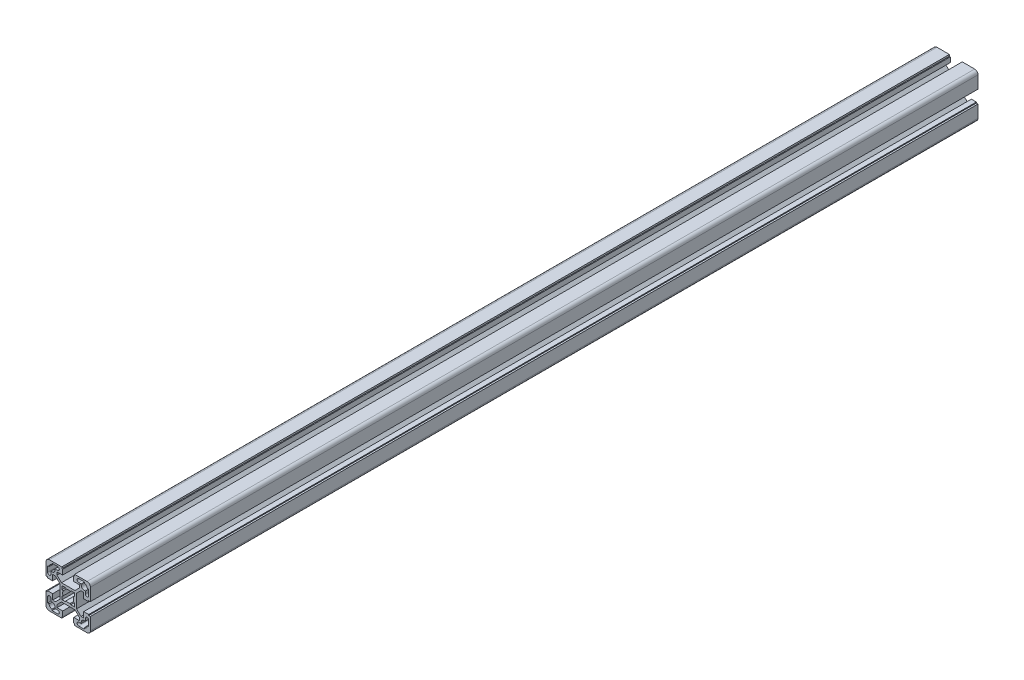
SolidWorks part; units mm, degrees
material "6061 Alloy"
ref_plane "Front Plane" through (0, 0, 0) normal (0, 0, 1) x (1, 0, 0)
ref_plane "Top Plane" through (0, 0, 0) normal (0, 1, 0) x (1, 0, 0)
ref_plane "Right Plane" through (0, 0, 0) normal (1, 0, 0) x (0, 0, -1)
sketch "Sketch1" plane through (0, 0, 0) normal (0, 0, 1) x (1, 0, 0)
  line L0 (5.8, -20) -> (17, -20)
  line L1 (14, -10.05) -> (11.4642, -10.05)
  line L2 (0, -21.1722) -> (0, 18.817) construction
  line L3 (0, 21.1722) -> (0, -18.817) construction
  line L4 (14.5, -18.5) -> (9.5, -18.5)
  line L5 (18.5, 5) -> (14, 5)
  line L6 (6.0858, -7.5) -> (10.05, -11.4642)
  line L7 (20, 5.8) -> (18.5, 5.8)
  line L8 (14, 5) -> (14, 10.05)
  line L9 (18.5, 5.8) -> (18.5, 5)
  line L10 (18.5, 14.5) -> (17.25, 14.5)
  line L11 (14.5, 11.75) -> (15.5, 11.75)
  line L12 (14.5, 17.25) -> (14.5, 18.5)
  line L13 (18.5, 9.5) -> (18.5, 14.5)
  line L14 (15.5, 11.75) -> (15.5, 9.5)
  line L15 (20, 17) -> (20, 5.8)
  line L16 (5.5, 5.5) -> (2.3979, 5.5)
  line L17 (2.3979, 5.5) -> (1.9983, 4.5833)
  line L18 (5.5, 2.3979) -> (5.5, 5.5)
  line L19 (4.5833, 1.9983) -> (5.5, 2.3979)
  line L20 (5, -14) -> (5, -18.5)
  line L21 (11.4642, 10.05) -> (7.5, 6.0858)
  line L22 (-6.0858, 7.5) -> (6.0858, 7.5)
  line L23 (11.75, 15.5) -> (11.75, 14.5)
  line L24 (5, -18.5) -> (5.8, -18.5)
  line L25 (5.8, -18.5) -> (5.8, -20)
  line L26 (10.05, -11.4642) -> (10.05, -14)
  line L27 (10.05, -14) -> (5, -14)
  line L28 (9.5, -15.5) -> (11.75, -15.5)
  line L29 (11.75, -15.5) -> (11.75, -14.5)
  line L30 (9.5, 15.5) -> (11.75, 15.5)
  line L31 (10.05, 14) -> (5, 14)
  line L32 (10.05, 11.4642) -> (10.05, 14)
  line L33 (5.8, 18.5) -> (5.8, 20)
  line L34 (5, 18.5) -> (5.8, 18.5)
  line L35 (7.5, -6.0858) -> (7.5, 6.0858)
  line L36 (5, 14) -> (5, 18.5)
  line L37 (6.0858, 7.5) -> (10.05, 11.4642)
  line L38 (14.5, 18.5) -> (9.5, 18.5)
  line L39 (14, 10.05) -> (11.4642, 10.05)
  line L40 (5.8, 20) -> (17, 20)
  line L41 (-18.5, -5) -> (-14, -5)
  line L42 (-6.0858, -7.5) -> (6.0858, -7.5)
  line L43 (11.4642, -10.05) -> (7.5, -6.0858)
  line L44 (-20, -5.8) -> (-18.5, -5.8)
  line L45 (-14, -5) -> (-14, -10.05)
  line L46 (-18.5, -5.8) -> (-18.5, -5)
  line L47 (-18.5, -14.5) -> (-17.25, -14.5)
  line L48 (4.5833, -1.9983) -> (5.5, -2.3979)
  line L49 (5.5, -2.3979) -> (5.5, -5.5)
  line L50 (2.3979, -5.5) -> (1.9983, -4.5833)
  line L51 (5.5, -5.5) -> (2.3979, -5.5)
  line L52 (-14.5, -11.75) -> (-15.5, -11.75)
  line L53 (-14.5, -17.25) -> (-14.5, -18.5)
  line L54 (-18.5, -9.5) -> (-18.5, -14.5)
  line L55 (-15.5, -11.75) -> (-15.5, -9.5)
  line L56 (-20, -17) -> (-20, -5.8)
  line L57 (-5.5, -5.5) -> (-2.3979, -5.5)
  line L58 (-2.3979, -5.5) -> (-1.9983, -4.5833)
  line L59 (-5.5, -2.3979) -> (-5.5, -5.5)
  line L60 (-4.5833, -1.9983) -> (-5.5, -2.3979)
  line L61 (-11.4642, -10.05) -> (-7.5, -6.0858)
  line L62 (-5.8, 20) -> (-17, 20)
  line L63 (-14, 10.05) -> (-11.4642, 10.05)
  line L64 (-14.5, 18.5) -> (-9.5, 18.5)
  line L65 (-6.0858, 7.5) -> (-10.05, 11.4642)
  line L66 (-5, 14) -> (-5, 18.5)
  line L67 (-7.5, -6.0858) -> (-7.5, 6.0858)
  line L68 (-5, 18.5) -> (-5.8, 18.5)
  line L69 (-5.8, 18.5) -> (-5.8, 20)
  line L70 (-10.05, 11.4642) -> (-10.05, 14)
  line L71 (-10.05, 14) -> (-5, 14)
  line L72 (-9.5, 15.5) -> (-11.75, 15.5)
  line L73 (-11.75, -15.5) -> (-11.75, -14.5)
  line L74 (-9.5, -15.5) -> (-11.75, -15.5)
  line L75 (-10.05, -14) -> (-5, -14)
  line L76 (-10.05, -11.4642) -> (-10.05, -14)
  line L77 (-5.8, -18.5) -> (-5.8, -20)
  line L78 (-5, -18.5) -> (-5.8, -18.5)
  line L79 (-11.75, 15.5) -> (-11.75, 14.5)
  line L80 (-11.4642, 10.05) -> (-7.5, 6.0858)
  line L81 (-5, -14) -> (-5, -18.5)
  line L82 (-4.5833, 1.9983) -> (-5.5, 2.3979)
  line L83 (-5.5, 2.3979) -> (-5.5, 5.5)
  line L84 (-2.3979, 5.5) -> (-1.9983, 4.5833)
  line L85 (-5.5, 5.5) -> (-2.3979, 5.5)
  line L86 (-20, 17) -> (-20, 5.8)
  line L87 (-15.5, 11.75) -> (-15.5, 9.5)
  line L88 (20, -17) -> (20, -5.8)
  line L89 (15.5, -11.75) -> (15.5, -9.5)
  line L90 (18.5, -9.5) -> (18.5, -14.5)
  line L91 (14.5, -17.25) -> (14.5, -18.5)
  line L92 (14.5, -11.75) -> (15.5, -11.75)
  line L93 (18.5, -14.5) -> (17.25, -14.5)
  line L94 (-18.5, 9.5) -> (-18.5, 14.5)
  line L95 (-14.5, 17.25) -> (-14.5, 18.5)
  line L96 (18.5, -5.8) -> (18.5, -5)
  line L97 (14, -5) -> (14, -10.05)
  line L98 (20, -5.8) -> (18.5, -5.8)
  line L99 (18.5, -5) -> (14, -5)
  line L100 (-14.5, 11.75) -> (-15.5, 11.75)
  line L101 (-18.5, 14.5) -> (-17.25, 14.5)
  line L102 (-18.5, 5.8) -> (-18.5, 5)
  line L103 (-14, 5) -> (-14, 10.05)
  line L104 (-20, 5.8) -> (-18.5, 5.8)
  line L105 (-6.0858, -7.5) -> (-10.05, -11.4642)
  line L106 (-18.5, 5) -> (-14, 5)
  line L107 (-14.5, -18.5) -> (-9.5, -18.5)
  line L108 (-20, 0) -> (20.788, 0) construction
  line L109 (-14, -10.05) -> (-11.4642, -10.05)
  line L110 (-5.8, -20) -> (-17, -20)
  arc A0 (14.5, -11.75) -> (11.75, -14.5) centre (14.5, -14.5) ccw
  arc A1 (18.5, 9.5) -> (15.5, 9.5) centre (17, 9.5) cw
  arc A2 (14.5, 17.25) -> (17.25, 14.5) centre (14.5, 14.5) cw
  arc A3 (17, 20) -> (20, 17) centre (17, 17) cw
  arc A4 (-1.9983, 4.5833) -> (1.9983, 4.5833) centre (0, 0) cw
  arc A5 (9.5, 15.5) -> (9.5, 18.5) centre (9.5, 17) cw
  arc A6 (9.5, -15.5) -> (9.5, -18.5) centre (9.5, -17) ccw
  arc A7 (14.5, 11.75) -> (11.75, 14.5) centre (14.5, 14.5) cw
  arc A8 (4.5833, -1.9983) -> (4.5833, 1.9983) centre (0, 0) ccw
  arc A9 (-18.5, -9.5) -> (-15.5, -9.5) centre (-17, -9.5) cw
  arc A10 (-14.5, -17.25) -> (-17.25, -14.5) centre (-14.5, -14.5) cw
  arc A11 (-1.9983, -4.5833) -> (1.9983, -4.5833) centre (0, 0) ccw
  arc A12 (-17, -20) -> (-20, -17) centre (-17, -17) cw
  arc A13 (-4.5833, -1.9983) -> (-4.5833, 1.9983) centre (0, 0) cw
  arc A14 (-14.5, 11.75) -> (-11.75, 14.5) centre (-14.5, 14.5) ccw
  arc A15 (-9.5, -15.5) -> (-9.5, -18.5) centre (-9.5, -17) cw
  arc A16 (-9.5, 15.5) -> (-9.5, 18.5) centre (-9.5, 17) ccw
  arc A17 (-17, 20) -> (-20, 17) centre (-17, 17) ccw
  arc A18 (17, -20) -> (20, -17) centre (17, -17) ccw
  arc A19 (14.5, -17.25) -> (17.25, -14.5) centre (14.5, -14.5) ccw
  arc A20 (18.5, -9.5) -> (15.5, -9.5) centre (17, -9.5) ccw
  arc A21 (-14.5, 17.25) -> (-17.25, 14.5) centre (-14.5, 14.5) ccw
  arc A22 (-18.5, 9.5) -> (-15.5, 9.5) centre (-17, 9.5) ccw
  arc A23 (-14.5, -11.75) -> (-11.75, -14.5) centre (-14.5, -14.5) cw
  point P55 (7.5, 0)
  point P101 (-7.5, 0)
  point P116 (0, -7.5)
  point P149 (0, 7.5)
extrude "Extrude1" add sketch "Sketch1" along normal blind 800
hole_wizard "M12 Tapped Hole1" [suppressed] positions "3DSketch2" profile "Sketch3" tap size "M12" standard "ISO"
sketch3d "3DSketch2"
  line L0 (-20, 17, 0) -> (-20, 5.8, 0) construction
  line L1 (-5.8, 20, 0) -> (-17, 20, 0) construction
  line L2 (-5.8, 20, 200) -> (-17, 20, 200) construction
  line L3 (-20, 17, 200) -> (-20, 5.8, 200) construction
  point P0 (0, 0, 200)
  point P2 (0, 0, 0)
  dimension "D1" = 20
  dimension "D2" = 20
  dimension "D3" = 20
  dimension "D4" = 20
sketch "Sketch3" plane through (0, 0, 200) normal (1, 0, 0) x (0, -1, 0)
  line L0 (0, 0) -> (0, 35.8144)
  line L1 (0, 35.8144) -> (5.1, 32.75)
  line L2 (5.1, 32.75) -> (5.1, 0.925)
  line L3 (5.1, 0.925) -> (6.025, 0)
  line L5 (6.025, 0) -> (0, 0)
  line L6 (-5.1, 0.925) -> (-6.025, 0) construction
  line L10 (0, 35.8144) -> (-5.1, 32.75) construction
  line L11 (0, -6.35) -> (0, 107.95) construction
  dimension "Tap Drill Dia." = 10.2
  dimension "Tap Drill Depth" = 32.75
  dimension "Near C'Sink Dia." = 12.05
  dimension "Near C'Sink Angle" = 90
  dimension "Drill Angle" = 118
cosmetic thread "Hole Thread1" [suppressed] parameters "D1"=24, "D2"=12
cosmetic thread "Hole Thread2" [suppressed] parameters "D1"=24, "D2"=12
hole_wizard "Ø9.8 (9.8) Diameter Hole1" [suppressed] positions "3DSketch3" profile "Sketch4" hole size "Ø9.8" standard "ISO"
sketch3d "3DSketch3"
  line L0 (-5.8, 20, 200) -> (-17, 20, 200) construction
  line L1 (20, -17, 200) -> (20, -5.8, 200) construction
  line L2 (17, 20, 0) -> (5.8, 20, 0) construction
  line L3 (20, -17, 0) -> (20, -5.8, 0) construction
  point P0 (0, 20, 184)
  point P2 (20, 0, 184)
  point P4 (0, 20, 16)
  point P6 (20, 0, 16)
  dimension "D1" = 16
  dimension "D2" = 20
  dimension "D3" = 20
  dimension "D4" = 16
  dimension "D5" = 16
  dimension "D6" = 16
sketch "Sketch4" plane through (0, 20, 184) normal (1, 0, 0) x (0, 0, 1)
  line L0 (0, 0) -> (0, 40)
  line L1 (0, 40) -> (4.9, 40)
  line L2 (4.9, 40) -> (4.9, 0)
  line L5 (4.9, 0) -> (0, 0)
  line L11 (0, -6.35) -> (0, 107.95) construction
  dimension "Thru Hole Dia." = 9.8
  dimension "Thru Hole Depth" = 40
hole_wizard "Ø17.0 (17) Diameter Hole1" [suppressed] positions "3DSketch4" profile "Sketch5" hole size "Ø17.0" standard "ISO"
sketch3d "3DSketch4"
  line L0 (-5.8, 20, 200) -> (-17, 20, 200) construction
  line L1 (-5.8, 20, 0) -> (-17, 20, 0) construction
  point P0 (0, 20, 177.5)
  point P2 (0, 20, 22.5)
  dimension "D1" = 20
  dimension "D2" = 22.5
  dimension "D3" = 22.5
sketch "Sketch5" plane through (0, 20, 177.5) normal (1, 0, 0) x (0, 0, 1)
  line L0 (0, 0) -> (0, 40)
  line L1 (0, 40) -> (8.5, 40)
  line L2 (8.5, 40) -> (8.5, 0)
  line L5 (8.5, 0) -> (0, 0)
  line L11 (0, -6.35) -> (0, 107.95) construction
  dimension "Thru Hole Dia." = 17
  dimension "Thru Hole Depth" = 40
